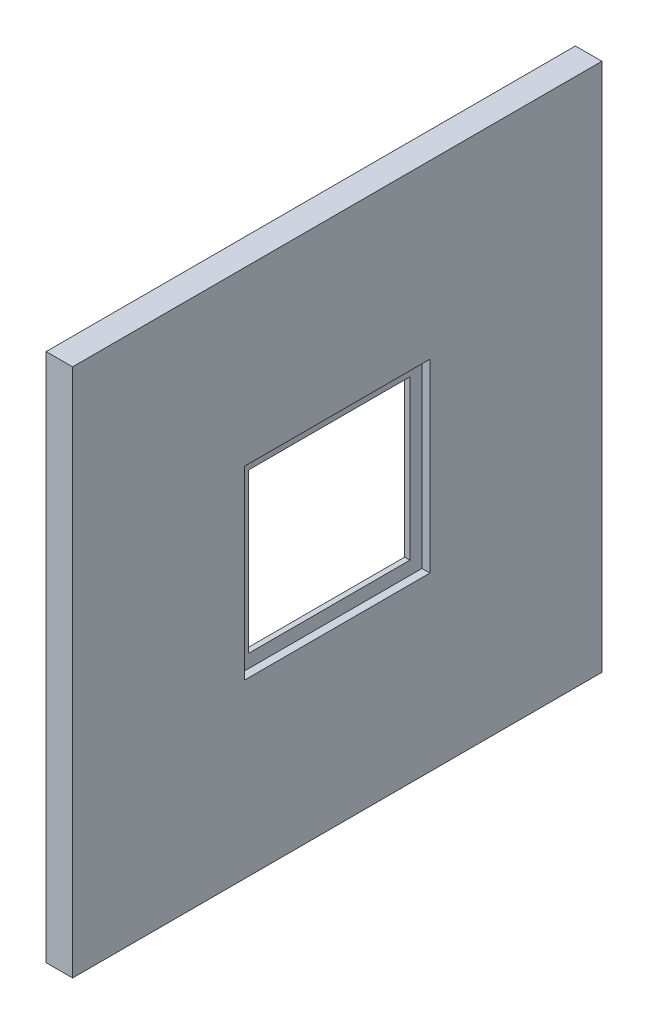
SolidWorks part; units mm, degrees
ref_plane "Front Plane" through (0, 0, 0) normal (0, 0, 1) x (1, 0, 0)
ref_plane "Top Plane" through (0, 0, 0) normal (0, 1, 0) x (1, 0, 0)
ref_plane "Right Plane" through (0, 0, 0) normal (1, 0, 0) x (0, 0, -1)
sketch "Sketch1" plane through (0, 0, 0) normal (1, 0, 0) x (0, 0, -1)
  line L1 (-100, 100) -> (100, 100)
  line L2 (-100, 100) -> (-100, -100)
  line L3 (-100, -100) -> (100, -100)
  line L4 (100, 100) -> (100, -100)
  point P4 (0, 100)
  point P6 (-100, 0)
  dimension "D1" = 200
  dimension "D2" = 200
extrude "Boss-Extrude1" add sketch "Sketch1" along normal blind 10
sketch "Sketch2" plane through (0, 0, 0) normal (-1, 0, 0) x (0, 0, 1)
  line L0 (-35.5, 35.5) -> (-25.5, 35.5)
  line L1 (-35.5, 35.5) -> (-25.5, 35.5)
  line L2 (-35.5, 35.5) -> (-35.5, -35.5)
  line L3 (-35.5, -35.5) -> (35.5, -35.5)
  line L4 (35.5, 35.5) -> (35.5, -35.5)
  line L5 (-25.5, 35.5) -> (-5, 44.5)
  line L6 (-5, 44.5) -> (5, 44.5)
  line L7 (5, 44.5) -> (25.5, 35.5)
  line L8 (25.5, 35.5) -> (35.5, 35.5)
  line L9 (25.5, 35.5) -> (35.5, 35.5)
  line L10 (36.5, 35.5) -> (36.5, -36.5)
  line L11 (-36.5, -36.5) -> (36.5, -36.5)
  line L12 (-36.5, 35.5) -> (-36.5, -36.5)
  line L13 (-35.5, 36.5) -> (-25.5, 36.5)
  line L14 (-25.902, 36.4156) -> (-5.2098, 45.5)
  line L15 (-5.2098, 45.5) -> (5.2098, 45.5)
  line L16 (5.2098, 45.5) -> (25.902, 36.4156)
  line L17 (25.5, 36.5) -> (35.5, 36.5)
  line L18 (-36.5, 35.5) -> (-36.5, 36.5)
  line L19 (-36.5, 36.5) -> (-35.5, 36.5)
  line L20 (35.5, 36.5) -> (36.5, 36.5)
  line L21 (36.5, 36.5) -> (36.5, 35.5)
  point P5 (0, -35.5)
  point P12 (35.5, 0)
  dimension "D1" = 10
  dimension "D2" = 71
  dimension "D3" = 71
  dimension "D4" = 10
  dimension "D5" = 10
  dimension "D6" = 80
  dimension "D7" = 20.5
  dimension "D8" = 1
extrude "Cut-Extrude1" cut sketch "Sketch2" against normal blind 5
sketch "Sketch3" plane through (5, 0, 0) normal (-1, 0, 0) x (0, 0, 1)
  line L1 (-30.5108, 30) -> (30.5108, 30)
  line L2 (-30.5108, 30) -> (-30.5108, -30)
  line L3 (-30.5108, -30) -> (30.5108, -30)
  line L4 (30.5108, 30) -> (30.5108, -30)
  point P4 (0, -30)
  point P6 (30.5108, 0)
  dimension "D1" = 60
  dimension "D2" = 61.0215
extrude "Cut-Extrude2" cut sketch "Sketch3" against normal through all
sketch "Sketch4" plane through (10, 0, 0) normal (1, 0, 0) x (0, 0, -1)
  line L1 (-35, 35) -> (35, 35)
  line L2 (-35, 35) -> (-35, -35)
  line L3 (-35, -35) -> (35, -35)
  line L4 (35, 35) -> (35, -35)
  point P4 (-35, 0)
  point P6 (0, -35)
  dimension "D1" = 70
  dimension "D2" = 70
extrude "Cut-Extrude3" cut sketch "Sketch4" against normal blind 3
